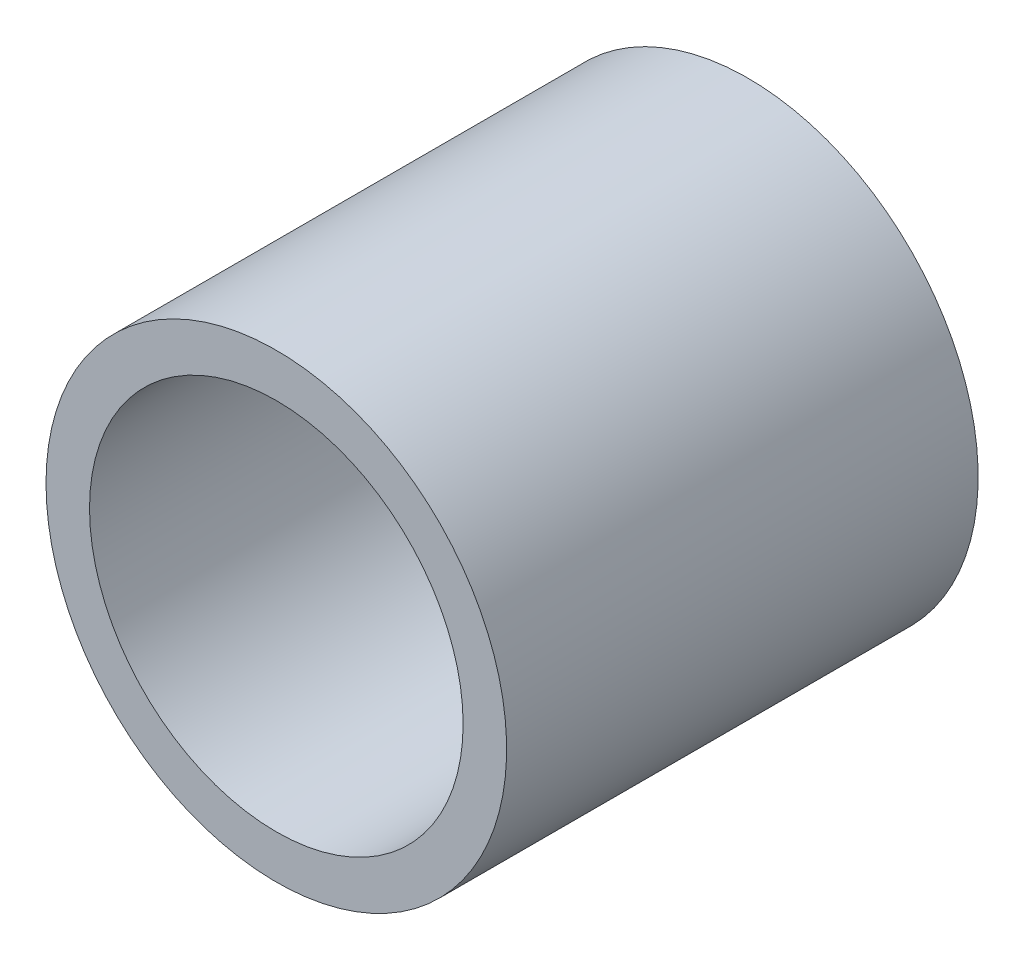
SolidWorks part; units mm, degrees
material "Tubo redondo com costura - 1/2\" x 1,2"
ref_plane "Plano frontal" through (0, 0, 0) normal (0, 0, 1) x (1, 0, 0)
ref_plane "Plano superior" through (0, 0, 0) normal (0, 1, 0) x (1, 0, 0)
ref_plane "Plano direito" through (0, 0, 0) normal (1, 0, 0) x (0, 0, -1)
sketch "Esboço1" plane through (0, 0, 0) normal (0, 0, 1) x (1, 0, 0)
  circle A0 centre (0, 0) radius 6.35
  circle A1 centre (0, 0) radius 5.15
  dimension "D1" = 12.7
  dimension "D2" = 1.2
extrude "Ressalto-extrusão1" add sketch "Esboço1" along normal blind 13
